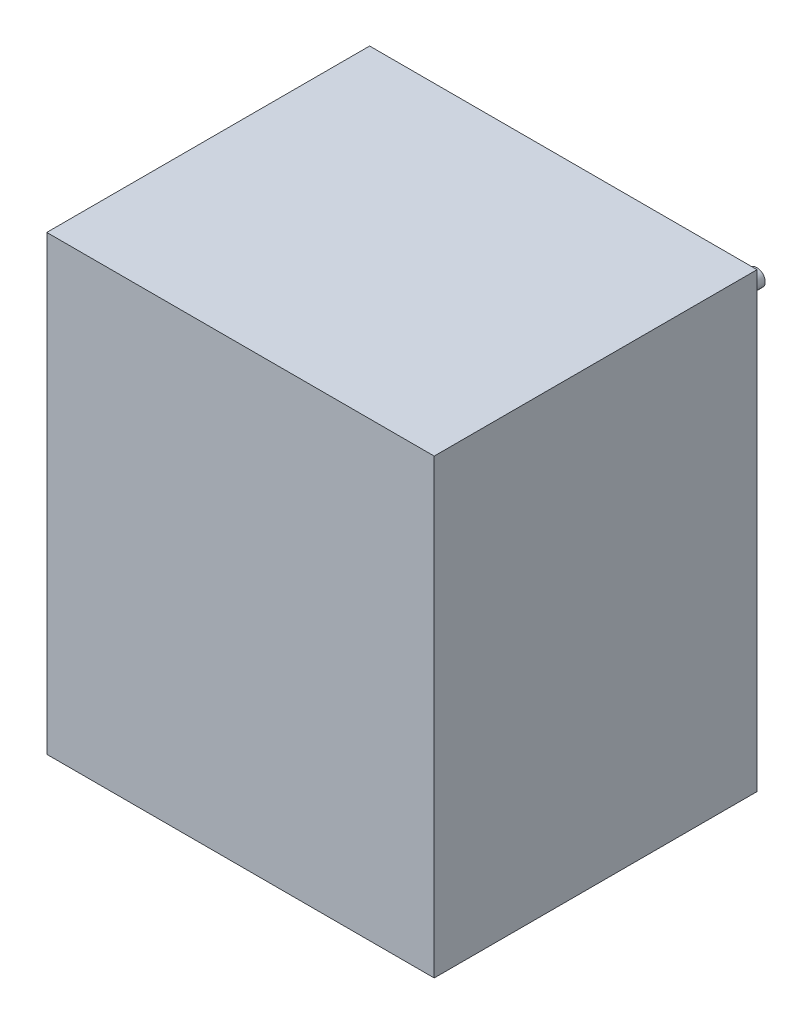
SolidWorks part; units mm, degrees
ref_plane "Alzado" through (0, 0, 0) normal (0, 0, 1) x (1, 0, 0)
ref_plane "Planta" through (0, 0, 0) normal (0, 1, 0) x (1, 0, 0)
ref_plane "Vista lateral" through (0, 0, 0) normal (1, 0, 0) x (0, 0, -1)
sketch "Croquis1" plane through (0, 0, 0) normal (0, 0, 1) x (1, 0, 0)
  line L1 (0, 0) -> (600, 0)
  line L2 (0, 0) -> (0, 700)
  line L3 (0, 700) -> (600, 700)
  line L4 (600, 0) -> (600, 700)
  dimension "D1" = 700
  dimension "D2" = 600
extrude "Saliente-Extruir1" add sketch "Croquis1" along normal blind 500
sketch "Croquis2" plane through (0, 0, 0) normal (-1, 0, 0) x (0, 0, 1)
  line L0 (500, 0) -> (0, 0) construction
  line L1 (0, 700) -> (0, 0) construction
  circle A0 centre (40, 30) radius 12.7
  dimension "D1" = 25.4
  dimension "D2" = 30
  dimension "D3" = 40
extrude "Saliente-Extruir2" add sketch "Croquis2" along normal blind 10
sketch3d "Croquis3D1"
  line L0 (-10, 30, 40) -> (-40, 30, 40)
  line L1 (-10, 30, 40) -> (0, 30, 40) construction
  line L2 (-60, 30, 20) -> (-60, 30, -660)
  arc A0 (-40, 30, 40) -> (-60, 30, 20) centre (-40, 30, 20) ccw
  point P7 (-60, 30, 40)
  point P8 (-40, 10, 20)
  dimension "D3" = 20
  dimension "D1" = 50
  dimension "D2" = 700
sketch "Croquis3" plane through (-10, 0, 0) normal (-1, 0, 0) x (0, 0, 1)
  circle A0 centre (40, 30) radius 12.7
sweep "Barrer1" add profiles "Croquis3" path "Croquis3D1"
